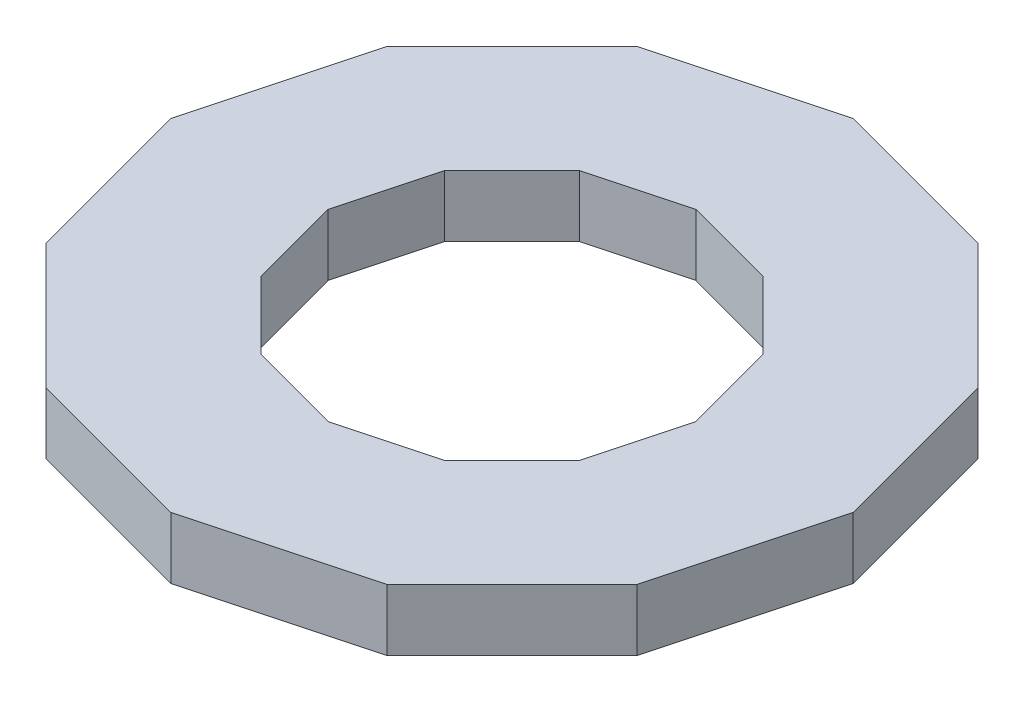
SolidWorks part; units mm, degrees
ref_plane "Front Plane" through (0, 0, 0) normal (0, 0, 1) x (1, 0, 0)
ref_plane "Top Plane" through (0, 0, 0) normal (0, 1, 0) x (1, 0, 0)
ref_plane "Right Plane" through (0, 0, 0) normal (1, 0, 0) x (0, 0, -1)
sketch "Sketch1" plane through (0, 0, 0) normal (0, 1, 0) x (1, 0, 0)
  line L0 (0, 0) -> (56.8508, 0) construction
  line L1 (56.8508, 0) -> (49.2342, 28.4254)
  line L2 (49.2342, 28.4254) -> (28.4254, 49.2342)
  line L3 (28.4254, 49.2342) -> (0, 56.8508)
  line L4 (0, 56.8508) -> (-28.4254, 49.2342)
  line L5 (-28.4254, 49.2342) -> (-49.2342, 28.4254)
  line L6 (-49.2342, 28.4254) -> (-56.8508, 0)
  line L7 (-56.8508, 0) -> (-49.2342, -28.4254)
  line L8 (-49.2342, -28.4254) -> (-28.4254, -49.2342)
  line L9 (-28.4254, -49.2342) -> (0, -56.8508)
  line L10 (0, -56.8508) -> (28.4254, -49.2342)
  line L11 (28.4254, -49.2342) -> (49.2342, -28.4254)
  line L12 (49.2342, -28.4254) -> (56.8508, 0)
  line L13 (105.4984, 0) -> (91.3643, 52.7492)
  line L14 (91.3643, 52.7492) -> (52.7492, 91.3643)
  line L15 (52.7492, 91.3643) -> (0, 105.4984)
  line L16 (0, 105.4984) -> (-52.7492, 91.3643)
  line L17 (-52.7492, 91.3643) -> (-91.3643, 52.7492)
  line L18 (-91.3643, 52.7492) -> (-105.4984, 0)
  line L19 (-105.4984, 0) -> (-91.3643, -52.7492)
  line L20 (-91.3643, -52.7492) -> (-52.7492, -91.3643)
  line L21 (-52.7492, -91.3643) -> (0, -105.4984)
  line L22 (0, -105.4984) -> (52.7492, -91.3643)
  line L23 (52.7492, -91.3643) -> (91.3643, -52.7492)
  line L24 (91.3643, -52.7492) -> (105.4984, 0)
  circle A0 centre (0, 0) radius 54.9136 construction
  circle A1 centre (0, 0) radius 101.9036 construction
  dimension "D1" = 46.99
  dimension "D2" = 54.61
extrude "Boss-Extrude1" add sketch "Sketch1" along normal blind 19.05
